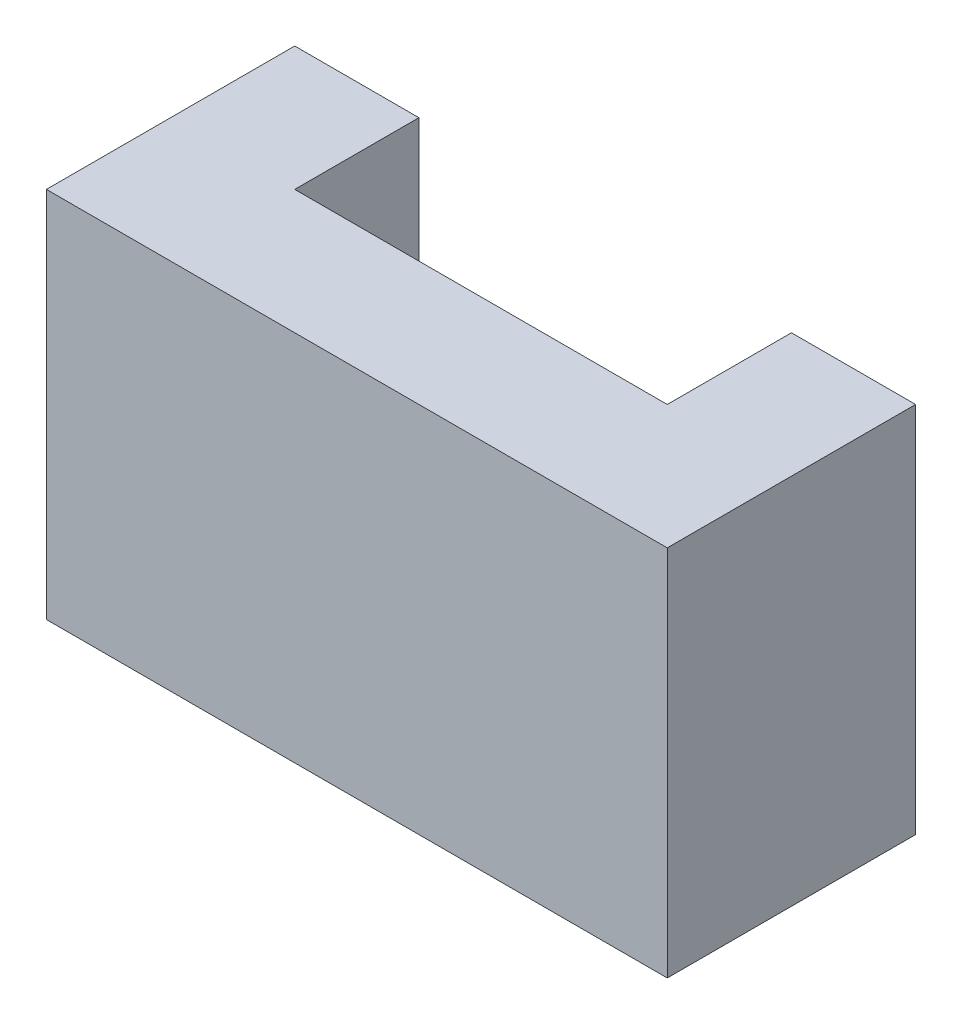
SolidWorks part; units mm, degrees
ref_plane "Přední rovina" through (0, 0, 0) normal (0, 0, 1) x (1, 0, 0)
ref_plane "Horní rovina" through (0, 0, 0) normal (0, 1, 0) x (1, 0, 0)
ref_plane "Pravá rovina" through (0, 0, 0) normal (1, 0, 0) x (0, 0, -1)
sketch "Sketch1" plane through (0, 0, 0) normal (0, 1, 0) x (1, 0, 0)
  line L1 (-25, 0) -> (-15, 0)
  line L2 (-25, 0) -> (-25, -20)
  line L3 (-25, -20) -> (25, -20)
  line L6 (-15, 0) -> (-15, -10)
  line L7 (-15, -10) -> (15, -10)
  line L9 (0, 0) -> (0, -20) construction
  line L10 (15, 0) -> (15, -10)
  line L11 (25, 0) -> (25, -20)
  line L12 (25, 0) -> (15, 0)
  point P3 (0, -10)
  dimension "D1" = 25
  dimension "D2" = 10
  dimension "D3" = 10
  dimension "D4" = 10
extrude "Boss-Extrude1" add sketch "Sketch1" along normal blind 30
